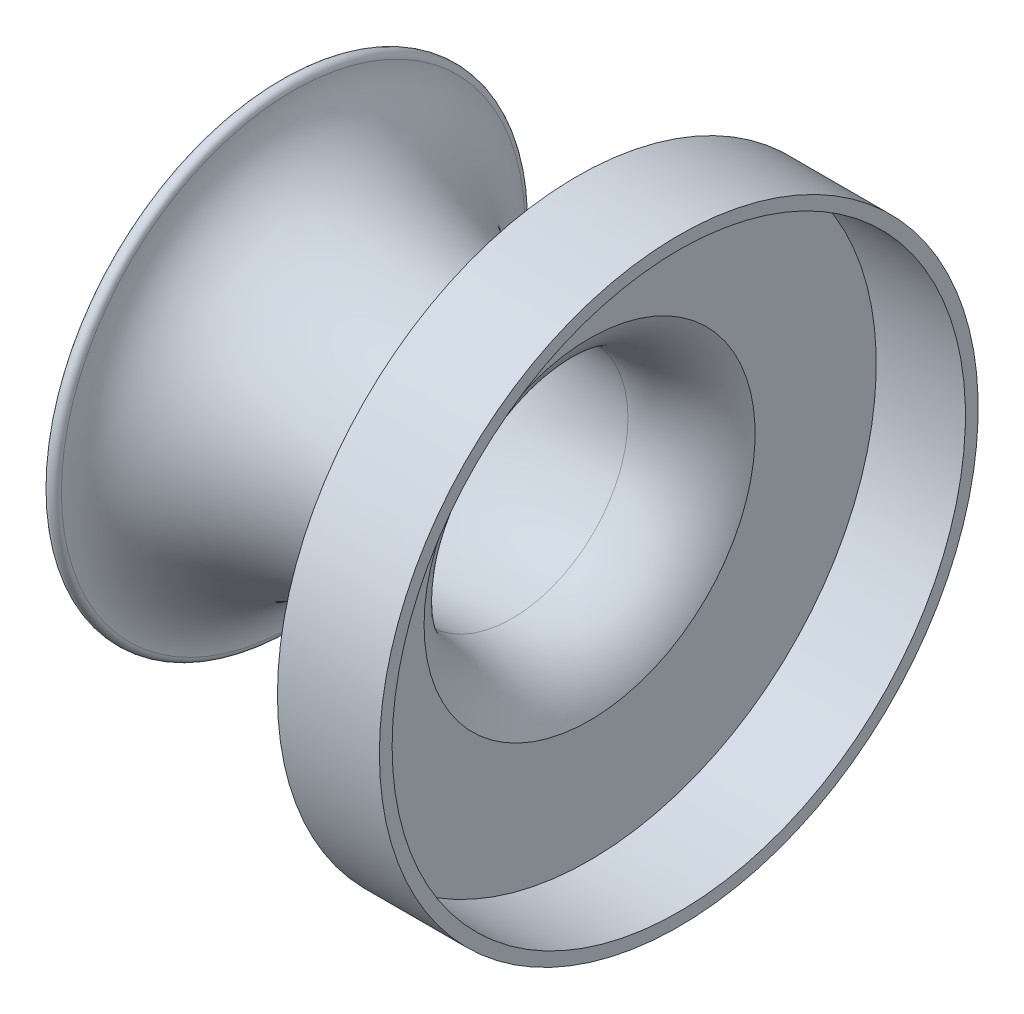
SolidWorks part; units mm, degrees
material "PVC 0.007 Plasticized"
ref_plane "Front Plane" through (0, 0, 0) normal (0, 0, 1) x (1, 0, 0)
ref_plane "Top Plane" through (0, 0, 0) normal (0, 1, 0) x (1, 0, 0)
ref_plane "Right Plane" through (0, 0, 0) normal (1, 0, 0) x (0, 0, -1)
sketch "Sketch1" plane through (0, 0, 0) normal (0, 0, 1) x (1, 0, 0)
  line L0 (15.4464, 33.0001) -> (15.4464, 57.15)
  line L1 (0, 33.0001) -> (24.7431, 33.0001) construction
  line L2 (15.4464, 57.15) -> (33.2264, 57.15)
  line L3 (0, 0) -> (54.525, 0) construction
  line L8 (12.9064, 33.5795) -> (12.9064, 59.69)
  line L9 (12.9064, 59.69) -> (33.2264, 59.69)
  line L10 (33.2264, 59.69) -> (33.2264, 57.15)
  circle A0 centre (0, 40.1) radius 17 construction
  arc A1 (0, 23.1) -> (15.4464, 33.0001) centre (0, 40.1) ccw
  arc A3 (0, 25.64) -> (12.9064, 33.5795) centre (0, 40.1) ccw
  arc A4 (-46.2001, 46.2001) -> (-43.6601, 46.2001) centre (-44.9301, 46.2001) cw
  ellipse E0 centre (0, 46.2001) end of major axis (46.2001, 46.2001) minor radius 23.1 (-46.2001, 46.2001) -> (0, 23.1) ccw
  ellipse E1 centre (0, 46.2001) end of major axis (-46.2001, 46.2001) minor radius 23.1 construction
  spline S0 degree 1 poles (-43.6601, 46.2001) (0, 25.64) knots 0 0 1 1 construction
  spline S1 degree 3 poles (-43.6601, 46.2001) (-43.6601, 45.6061) (-43.5448, 44.4326) (-42.8398, 42.0391) (-41.0017, 38.9713) (-37.1497, 35.3451) (-31.7524, 32.0484) (-25.0354, 29.2877) (-17.2811, 27.2141) (-8.8296, 25.9298) (-2.9241, 25.64) (0, 25.64) knots 3.141593 3.141593 3.141593 3.141593 3.239767 3.337942 3.534292 3.730641 3.926991 4.12334 4.31969 4.516039 4.712389 4.712389 4.712389 4.712389
  point P0 (0, 23.1)
  dimension "D3" = 17
  dimension "D1" = 33.0001
  dimension "D2" = 23.1
  dimension "D4" = 33.9999
  dimension "D5" = 57.15
  dimension "D6" = 17.78
  dimension "D8" = 23.1
  dimension "D9" = 0
  dimension "D7" = 2.54
revolve "Revolve1" add sketch "Sketch1" angle 360 about L3
